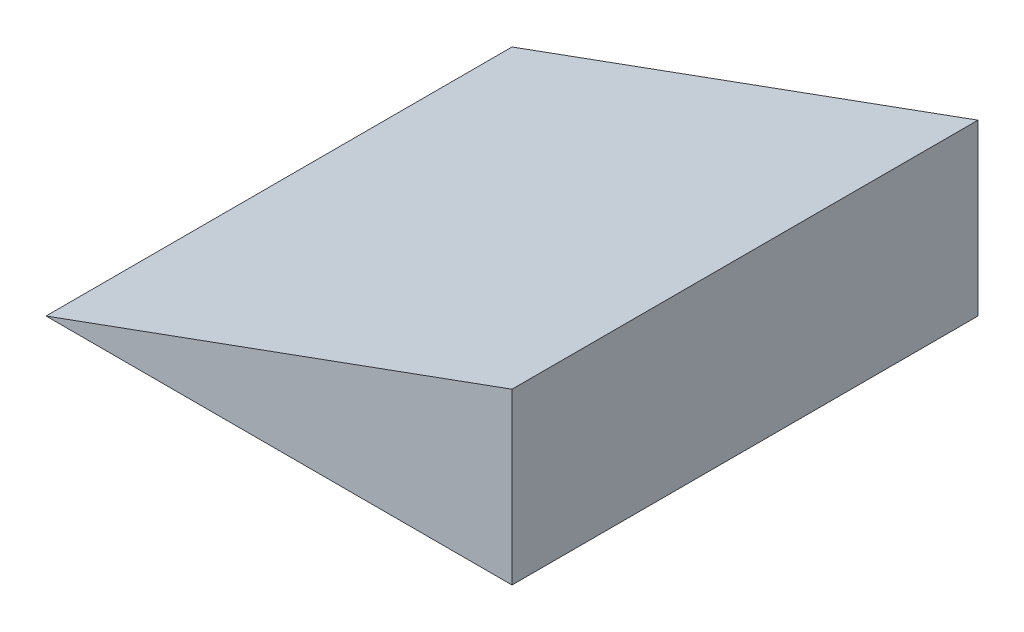
SolidWorks part; units mm, degrees
ref_plane "Front Plane" through (0, 0, 0) normal (0, 0, 1) x (1, 0, 0)
ref_plane "Top Plane" through (0, 0, 0) normal (0, 1, 0) x (1, 0, 0)
ref_plane "Right Plane" through (0, 0, 0) normal (1, 0, 0) x (0, 0, -1)
sketch "Sketch1" plane through (0, 0, 0) normal (0, 0, 1) x (1, 0, 0)
  line L0 (-2000, 0) -> (2000, 0)
  line L1 (-2000, 0) -> (2000, 1455.8809)
  line L2 (2000, 1455.8809) -> (2000, 0)
  point P4 (0, 0)
  dimension "D1" = 20
  dimension "D2" = 4000
extrude "Boss-Extrude1" add sketch "Sketch1" along normal blind 4000
